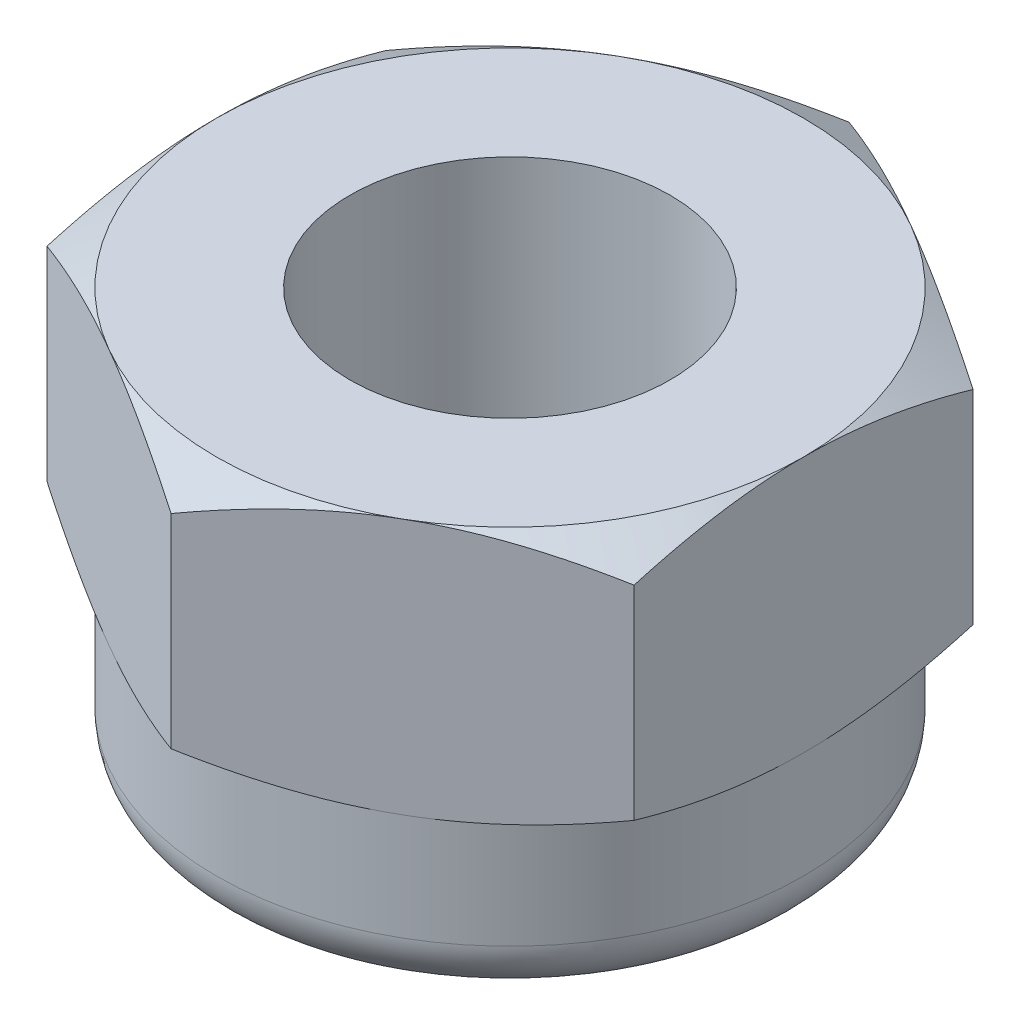
SolidWorks part; units mm, degrees
material "AISI 304"
ref_plane "前视基准面" through (0, 0, 0) normal (0, 0, 1) x (1, 0, 0)
ref_plane "上视基准面" through (0, 0, 0) normal (0, 1, 0) x (1, 0, 0)
ref_plane "右视基准面" through (0, 0, 0) normal (1, 0, 0) x (0, 0, -1)
sketch "草图1" plane through (0, 0, 0) normal (0, 1, 0) x (1, 0, 0)
  line L1 (2.75, 1.5877) -> (0, 3.1754)
  line L2 (0, 3.1754) -> (-2.75, 1.5877)
  line L3 (-2.75, 1.5877) -> (-2.75, -1.5877)
  line L4 (-2.75, -1.5877) -> (0, -3.1754)
  line L5 (0, -3.1754) -> (2.75, -1.5877)
  line L6 (2.75, -1.5877) -> (2.75, 1.5877)
  circle A0 centre (0, 0) radius 1.5
  circle A1 centre (0, 0) radius 2.75 construction
  dimension "D1" = 3
  dimension "D2" = 5.5
extrude "凸台-拉伸2" add sketch "草图1" along normal blind 2.4
cosmetic thread "装饰螺纹线1" parameters "D2"=22
sketch "草图2" plane through (0, 0, 0) normal (0, 0, 1) x (1, 0, 0)
  line L0 (2.75, 2.4) -> (4.8285, 2.4)
  line L1 (4.8285, 2.4) -> (4.8285, 1.2)
  line L2 (4.8285, 1.2) -> (2.75, 2.4)
  line L3 (2.75, 0) -> (4.8285, 0)
  line L4 (4.8285, 0) -> (4.8285, 1.2)
  line L5 (2.75, 0) -> (4.8285, 1.2)
  line L6 (0, 1.9814) -> (0, 2.9288) construction
  dimension "D1" = 30
  dimension "D2" = 30
revolve "切除-旋转1" cut sketch "草图2" angle 360 about L6
sketch "草图3" plane through (0, 0, 0) normal (0, -1, 0) x (1, 0, 0)
  circle A0 centre (0, 0) radius 2.75
  circle A1 centre (0, 0) radius 1.5
  dimension "D1" = 3
  dimension "D2" = 5.5
extrude "凸台-拉伸3" add sketch "草图3" along normal blind 1.5
fillet "圆角1" radius 0.5 1 edges at (0, -1.5, -2.75)
